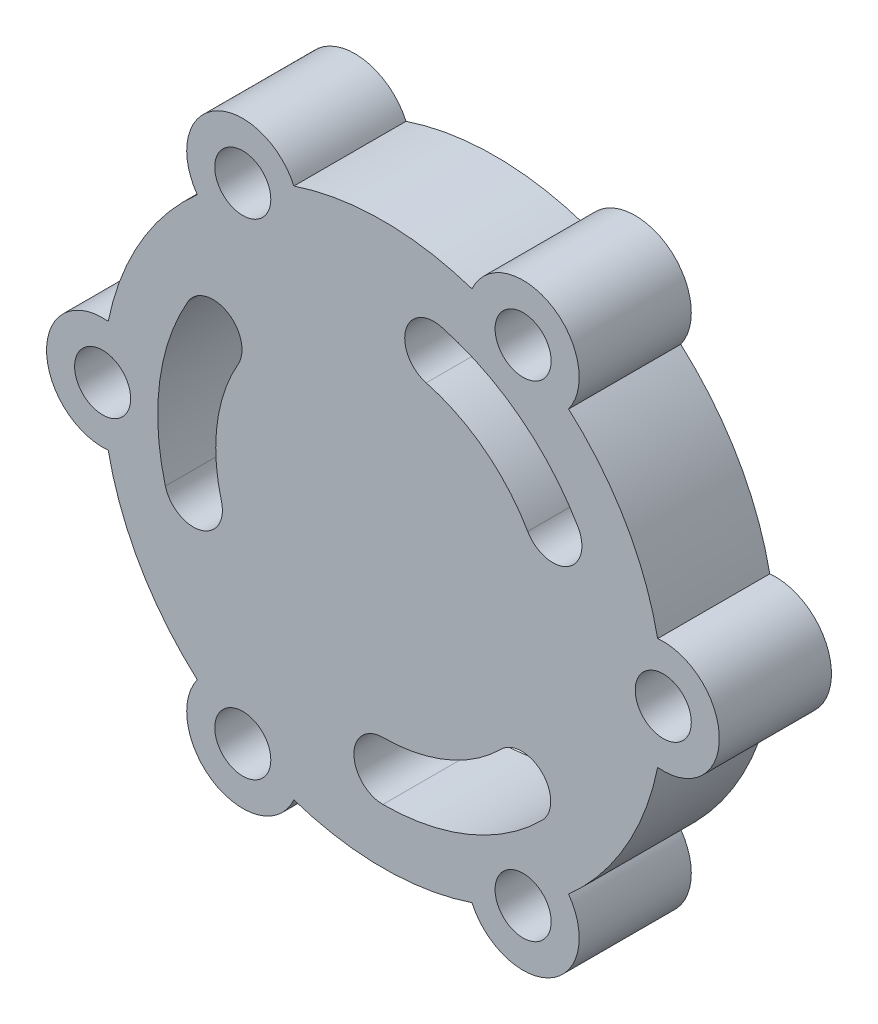
SolidWorks part; units mm, degrees
ref_plane "Front Plane" through (0, 0, 0) normal (0, 0, 1) x (1, 0, 0)
ref_plane "Top Plane" through (0, 0, 0) normal (0, 1, 0) x (1, 0, 0)
ref_plane "Right Plane" through (0, 0, 0) normal (1, 0, 0) x (0, 0, -1)
sketch "Sketch2" plane through (0, 0, 0) normal (0, 0, 1) x (1, 0, 0)
  line L0 (70, 70) -> (50070, 70) construction
  line L1 (70, 70) -> (43371.2702, 25070) construction
  arc A2 (85.8832, 117.4102) -> (54.1168, 117.4102) centre (70, 70) ccw
  circle A3 centre (70, 70) radius 35 construction
  arc A4 (119, 60.0501) -> (119, 79.9499) centre (120, 70) ccw
  circle A5 centre (120, 70) radius 5
  arc A6 (85.8832, 22.5898) -> (103.1168, 32.5397) centre (95, 26.6987) ccw
  circle A7 centre (95, 26.6987) radius 5
  arc A8 (36.8832, 32.5397) -> (54.1168, 22.5898) centre (45, 26.6987) ccw
  circle A9 centre (45, 26.6987) radius 5
  arc A10 (21, 79.9499) -> (21, 60.0501) centre (20, 70) ccw
  circle A11 centre (20, 70) radius 5
  arc A12 (54.1168, 117.4102) -> (36.8832, 107.4603) centre (45, 113.3013) ccw
  circle A13 centre (45, 113.3013) radius 5
  arc A14 (103.1168, 107.4603) -> (85.8832, 117.4102) centre (95, 113.3013) ccw
  circle A15 centre (95, 113.3013) radius 5
  arc A16 (36.8832, 107.4603) -> (21, 79.9499) centre (70, 70) ccw
  arc A17 (21, 60.0501) -> (36.8832, 32.5397) centre (70, 70) ccw
  arc A18 (54.1168, 22.5898) -> (85.8832, 22.5898) centre (70, 70) ccw
  arc A19 (103.1168, 32.5397) -> (119, 60.0501) centre (70, 70) ccw
  arc A20 (119, 79.9499) -> (103.1168, 107.4603) centre (70, 70) ccw
  arc A21 (79.0587, 103.8074) -> (100.3109, 87.5) centre (70, 70) cw construction
  arc A22 (104.7938, 90.0882) -> (80.3984, 108.8074) centre (70, 70) ccw
  arc A23 (95.828, 84.9118) -> (77.7189, 98.8074) centre (70, 70) ccw
  arc A24 (95.828, 84.9118) -> (104.7938, 90.0882) centre (100.3109, 87.5) ccw
  arc A25 (80.3984, 108.8074) -> (77.7189, 98.8074) centre (79.0587, 103.8074) ccw
  arc A26 (94.7487, 45.2513) -> (70, 35) centre (70, 70) cw construction
  arc A27 (70, 29.8236) -> (98.409, 41.591) centre (70, 70) ccw
  arc A28 (70, 40.1764) -> (91.0885, 48.9115) centre (70, 70) ccw
  arc A29 (70, 40.1764) -> (70, 29.8236) centre (70, 35) ccw
  arc A30 (98.409, 41.591) -> (91.0885, 48.9115) centre (94.7487, 45.2513) ccw
  arc A31 (36.1926, 60.9413) -> (39.6891, 87.5) centre (70, 70) cw construction
  arc A32 (35.2062, 90.0882) -> (31.1926, 59.6016) centre (70, 70) ccw
  arc A33 (44.172, 84.9118) -> (41.1926, 62.2811) centre (70, 70) ccw
  arc A34 (44.172, 84.9118) -> (35.2062, 90.0882) centre (39.6891, 87.5) ccw
  arc A35 (31.1926, 59.6016) -> (41.1926, 62.2811) centre (36.1926, 60.9413) ccw
  point P11 (91.3067, 97.7674)
  point P25 (70, 70)
  point P39 (70, 70)
  point P44 (83.3939, 37.6642)
  point P52 (35.2994, 74.5684)
  point P57 (70, 70)
  dimension "D3" = 100
  dimension "D4" = 70
  dimension "D5" = 10
  dimension "D6" = 20
  dimension "D1" = 70
  dimension "D2" = 70
  dimension "D8" = 30
  dimension "D9" = 45
  dimension "D10" = 10
  dimension "D7" = 6
  dimension "D11" = 3
extrude "Boss-Extrude1" add sketch "Sketch2" along normal mid plane 20
